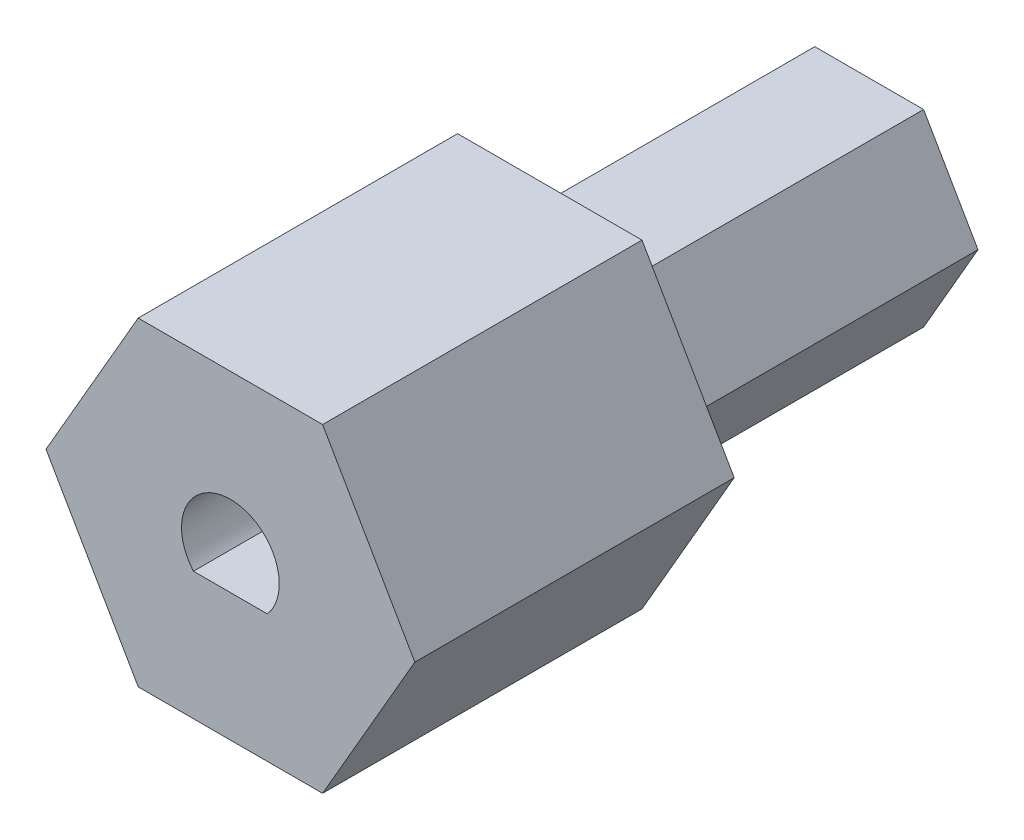
SolidWorks part; units mm, degrees
ref_plane "Front Plane" through (0, 0, 0) normal (0, 0, 1) x (1, 0, 0)
ref_plane "Top Plane" through (0, 0, 0) normal (0, 1, 0) x (1, 0, 0)
ref_plane "Right Plane" through (0, 0, 0) normal (1, 0, 0) x (0, 0, -1)
sketch "Sketch1" plane through (0, 0, 0) normal (0, 0, 1) x (1, 0, 0)
  line L1 (3.4064, 0) -> (1.7032, 2.95)
  line L2 (1.7032, 2.95) -> (-1.7032, 2.95)
  line L3 (-1.7032, 2.95) -> (-3.4064, 0)
  line L4 (-3.4064, 0) -> (-1.7032, -2.95)
  line L5 (-1.7032, -2.95) -> (1.7032, -2.95)
  line L6 (1.7032, -2.95) -> (3.4064, 0)
  circle A0 centre (0, 0) radius 2.95 construction
  dimension "D1" = 5.9
extrude "Boss-Extrude1" add sketch "Sketch1" along normal blind 20
sketch "Sketch2" plane through (0, 0, 20) normal (0, 0, 1) x (1, 0, 0)
  line L1 (-5.7735, 0) -> (-2.8868, -5)
  line L2 (-2.8868, -5) -> (2.8868, -5)
  line L3 (2.8868, -5) -> (5.7735, 0)
  line L4 (5.7735, 0) -> (2.8868, 5)
  line L5 (2.8868, 5) -> (-2.8868, 5)
  line L6 (-2.8868, 5) -> (-5.7735, 0)
  circle A0 centre (0, 0) radius 5 construction
  dimension "D1" = 10
extrude "Boss-Extrude2" add sketch "Sketch2" against normal blind 10 contours L1 L2 L3 L4 L5 L6
sketch "Sketch4" plane through (0, 0, 20) normal (0, 0, 1) x (1, 0, 0)
  line L0 (0, 0) -> (0, -1) construction
  line L1 (-1.158, -1) -> (1.158, -1)
  arc A0 (-1.158, -1) -> (1.158, -1) centre (0, 0) cw
  point P5 (0, 1.53)
  point P8 (0, -1)
  dimension "D1" = 1.53
  dimension "D2" = 1
  dimension "D3" = 2.53
extrude "Cut-Extrude1" cut sketch "Sketch4" against normal blind 11 contours L1 A0
